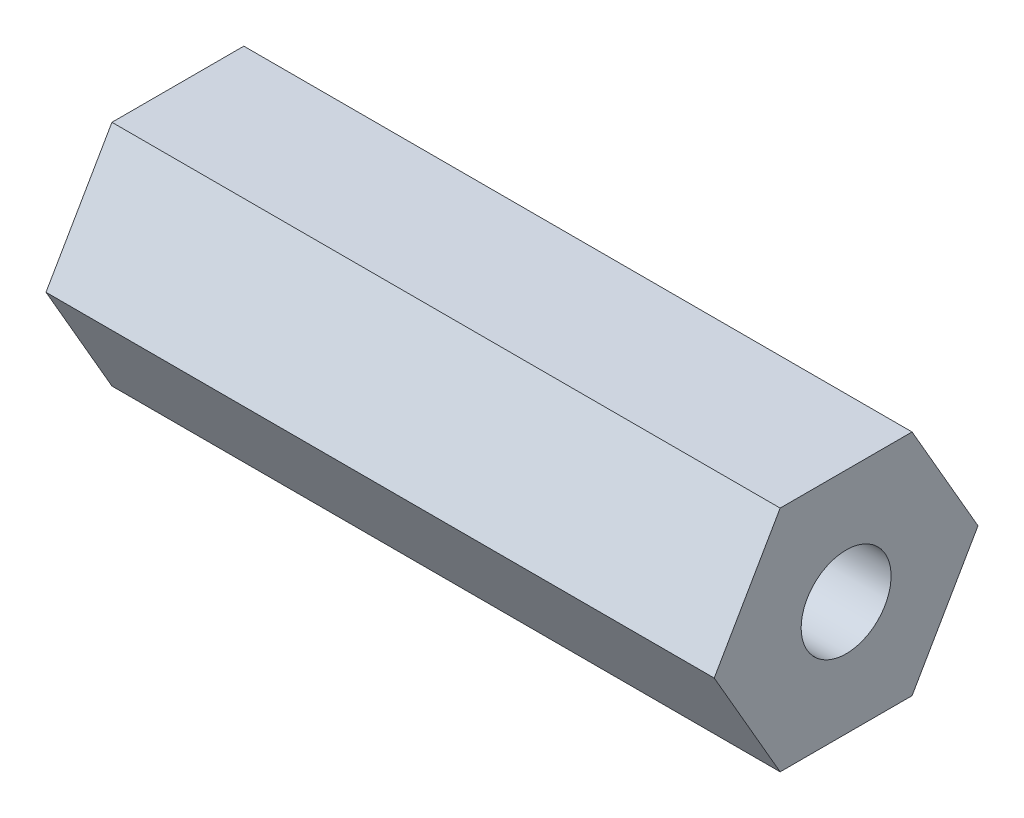
SolidWorks part; units mm, degrees
material "7075-T6 (SN)"
ref_plane "Front Plane" through (0, 0, 0) normal (0, 0, 1) x (1, 0, 0)
ref_plane "Top Plane" through (0, 0, 0) normal (0, 1, 0) x (1, 0, 0)
ref_plane "Right Plane" through (0, 0, 0) normal (1, 0, 0) x (0, 0, -1)
sketch "Sketch2" plane through (0, 0, 0) normal (1, 0, 0) x (0, 0, -1)
  line L1 (7.3323, 0) -> (3.6662, 6.35)
  line L2 (3.6662, 6.35) -> (-3.6662, 6.35)
  line L3 (-3.6662, 6.35) -> (-7.3323, 0)
  line L4 (-7.3323, 0) -> (-3.6662, -6.35)
  line L5 (-3.6662, -6.35) -> (3.6662, -6.35)
  line L6 (3.6662, -6.35) -> (7.3323, 0)
  circle A0 centre (0, 0) radius 6.35 construction
  dimension "D1" = 12.7
extrude "Boss-Extrude1" add sketch "Sketch2" along normal mid plane 37.15
sketch "Sketch3" plane through (-18.575, 0, 0) normal (-1, 0, 0) x (0, 0, 1)
  circle A0 centre (0, 0) radius 2.5
  dimension "D1" = 5
extrude "Cut-Extrude1" cut sketch "Sketch3" against normal through all
